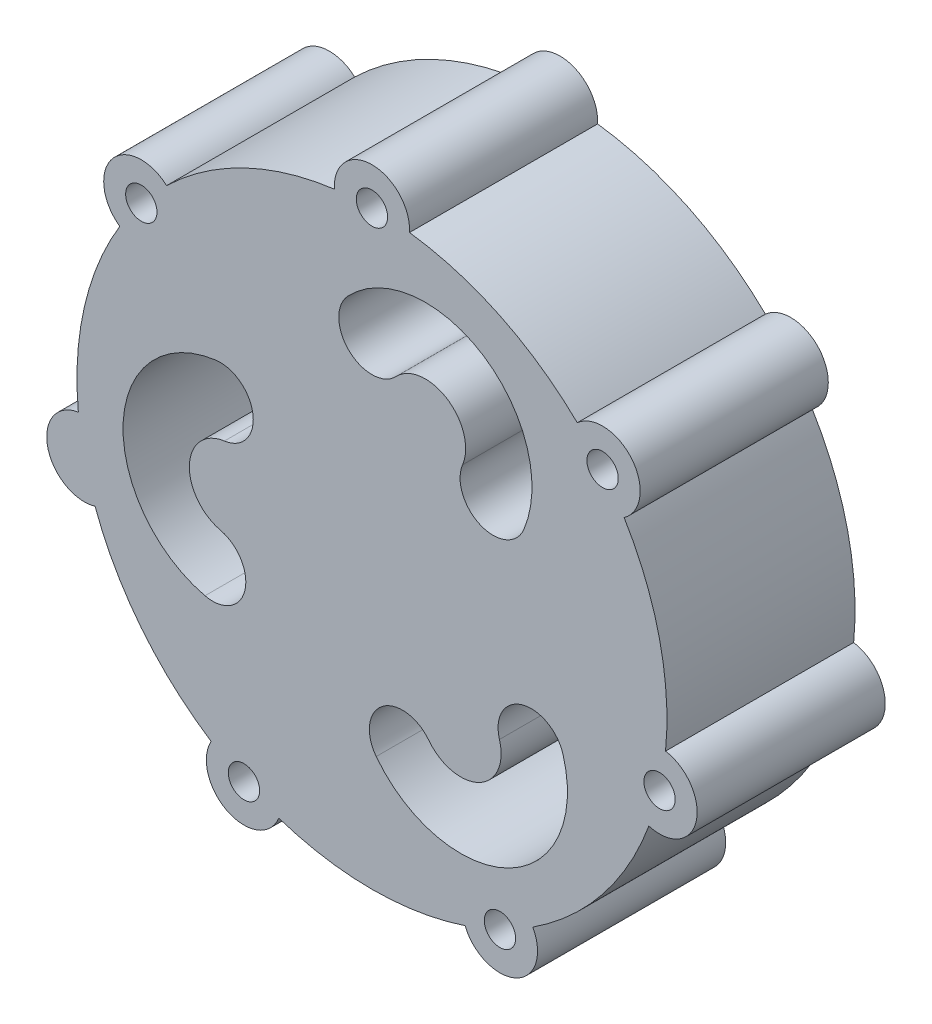
SolidWorks part; units mm, degrees
ref_plane "Front Plane" through (0, 0, 0) normal (0, 0, 1) x (1, 0, 0)
ref_plane "Top Plane" through (0, 0, 0) normal (0, 1, 0) x (1, 0, 0)
ref_plane "Right Plane" through (0, 0, 0) normal (1, 0, 0) x (0, 0, -1)
sketch "Sketch1" plane through (0, 0, 0) normal (0, 0, 1) x (1, 0, 0)
  line L0 (-944.6041, 0) -> (46285.6003, 0) construction
  line L1 (0, -944.6041) -> (0, 46285.6003) construction
  arc A1 (5.9878, 46.6628) -> (-5.9878, 46.6628) centre (0, 47.0455) ccw
  circle A2 centre (0, 47.0455) radius 2.5
  circle A3 centre (36.7816, 29.3324) radius 2.5
  arc A4 (40.2158, 24.4124) -> (32.7492, 33.7753) centre (36.7816, 29.3324) ccw
  circle A5 centre (45.8659, -10.4686) radius 2.5
  arc A6 (44.1605, -16.2211) -> (46.8253, -4.5458) centre (45.8659, -10.4686) ccw
  circle A7 centre (20.4123, -42.3865) radius 2.5
  arc A8 (14.8514, -44.6398) -> (25.6411, -39.4438) centre (20.4123, -42.3865) ccw
  circle A9 centre (-20.4123, -42.3865) radius 2.5
  arc A10 (-25.6411, -39.4438) -> (-14.8514, -44.6398) centre (-20.4123, -42.3865) ccw
  arc A11 (-46.3573, -8.0174) -> (-45.2451, -12.8903) centre (-45.8659, -10.4686) ccw
  arc A12 (-46.8253, -4.5458) -> (-44.1605, -16.2211) centre (-45.8659, -10.4686) ccw
  circle A13 centre (-36.7816, 29.3324) radius 2.5
  arc A14 (-32.7492, 33.7753) -> (-40.2158, 24.4124) centre (-36.7816, 29.3324) ccw
  arc A15 (-40.2158, 24.4124) -> (-46.8253, -4.5458) centre (0, 0) ccw
  arc A16 (-44.1605, -16.2211) -> (-25.6411, -39.4438) centre (0, 0) ccw
  arc A17 (32.7492, 33.7753) -> (5.9878, 46.6628) centre (0, 0) ccw
  arc A18 (46.8253, -4.5458) -> (40.2158, 24.4124) centre (0, 0) ccw
  arc A19 (-14.8514, -44.6398) -> (14.8514, -44.6398) centre (0, 0) ccw
  arc A20 (-5.9878, 46.6628) -> (-32.7492, 33.7753) centre (0, 0) ccw
  arc A21 (25.6411, -39.4438) -> (44.1605, -16.2211) centre (0, 0) ccw
  arc A22 (0, 29.3324) -> (19.3415, 16.7951) centre (8.5176, 21.2848) cw construction
  arc A27 (25.4026, -14.6662) -> (4.8742, -25.1478) centre (14.1743, -18.0189) cw construction
  arc A32 (0.6776, -28.3646) -> (30.4692, -13.1533) centre (14.1743, -18.0189) ccw
  arc A37 (24.2257, 14.7691) -> (-3.8435, 32.9637) centre (8.5176, 21.2848) ccw
  arc A38 (14.4574, 18.821) -> (3.8435, 25.701) centre (8.5176, 21.2848) ccw
  arc A39 (14.4574, 18.821) -> (24.2257, 14.7691) centre (19.3415, 16.7951) ccw
  arc A40 (-3.8435, 32.9637) -> (3.8435, 25.701) centre (0, 29.3324) ccw
  arc A41 (9.0708, -21.9309) -> (20.336, -16.179) centre (14.1743, -18.0189) ccw
  arc A42 (9.0708, -21.9309) -> (0.6776, -28.3646) centre (4.8742, -25.1478) ccw
  arc A43 (30.4692, -13.1533) -> (20.336, -16.179) centre (25.4026, -14.6662) ccw
  arc A44 (-25.4026, -14.6662) -> (-24.2157, 8.3527) centre (-22.692, -3.2659) cw construction
  arc A45 (-24.9033, 13.5955) -> (-26.6257, -19.8104) centre (-22.692, -3.2659) ccw
  arc A46 (-23.5281, 3.1099) -> (-24.1794, -9.5219) centre (-22.692, -3.2659) ccw
  arc A47 (-23.5281, 3.1099) -> (-24.9033, 13.5955) centre (-24.2157, 8.3527) ccw
  arc A48 (-26.6257, -19.8104) -> (-24.1794, -9.5219) centre (-25.4026, -14.6662) ccw
  point P39 (14.8915, 31.1178)
  point P48 (19.5031, -28.4553)
  point P56 (-34.3945, -2.6625)
  dimension "D1" = 12
  dimension "D2" = 5
  dimension "D3" = 7
  dimension "D4" = 3
extrude "Boss-Extrude1" add sketch "Sketch1" along normal blind 30
